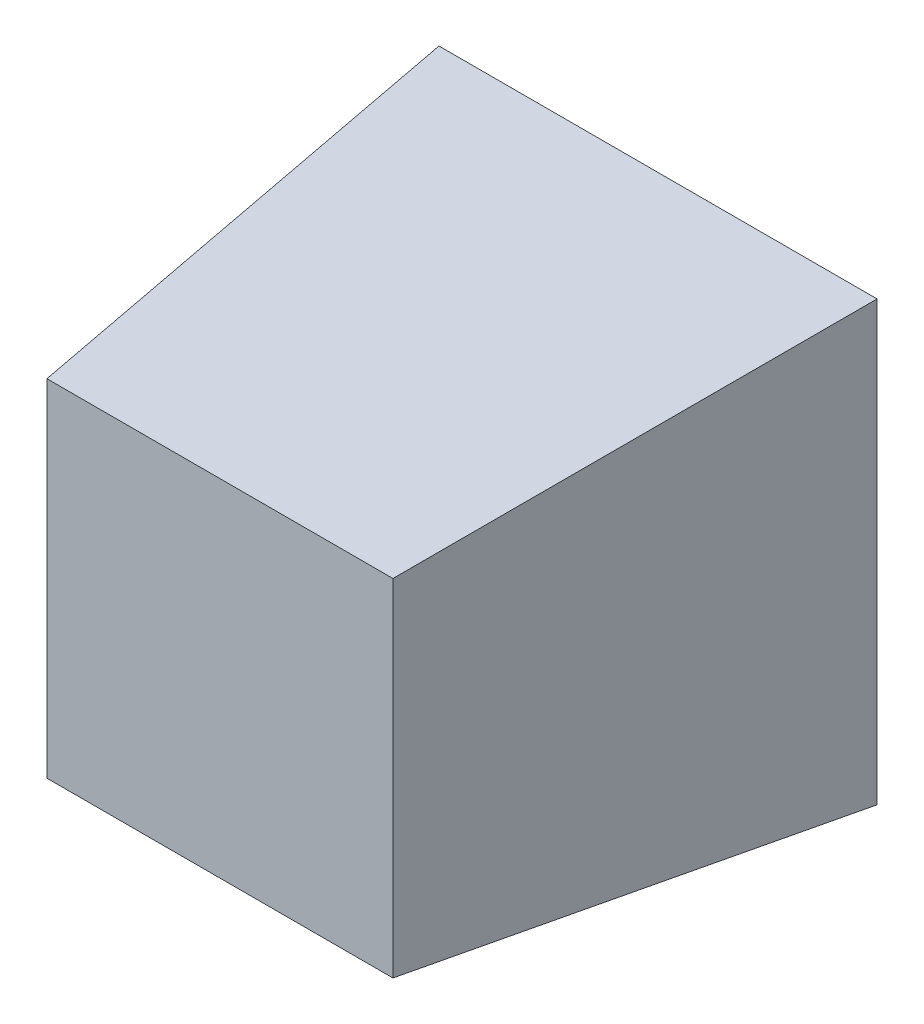
SolidWorks part; units mm, degrees
ref_plane "前视基准面" through (0, 0, 0) normal (0, 0, 1) x (1, 0, 0)
ref_plane "上视基准面" through (0, 0, 0) normal (0, 1, 0) x (1, 0, 0)
ref_plane "右视基准面" through (0, 0, 0) normal (1, 0, 0) x (0, 0, -1)
other "Configuration Table"
sketch "草图1" plane through (0, 0, 0) normal (0, 0, 1) x (1, 0, 0)
  line L1 (0, 0) -> (10, 0)
  line L2 (0, 0) -> (0, 10)
  line L3 (0, 10) -> (10, 10)
  line L4 (10, 0) -> (10, 10)
extrude "凸台-拉伸1" add sketch "草图1" along normal blind 10 draft 6
